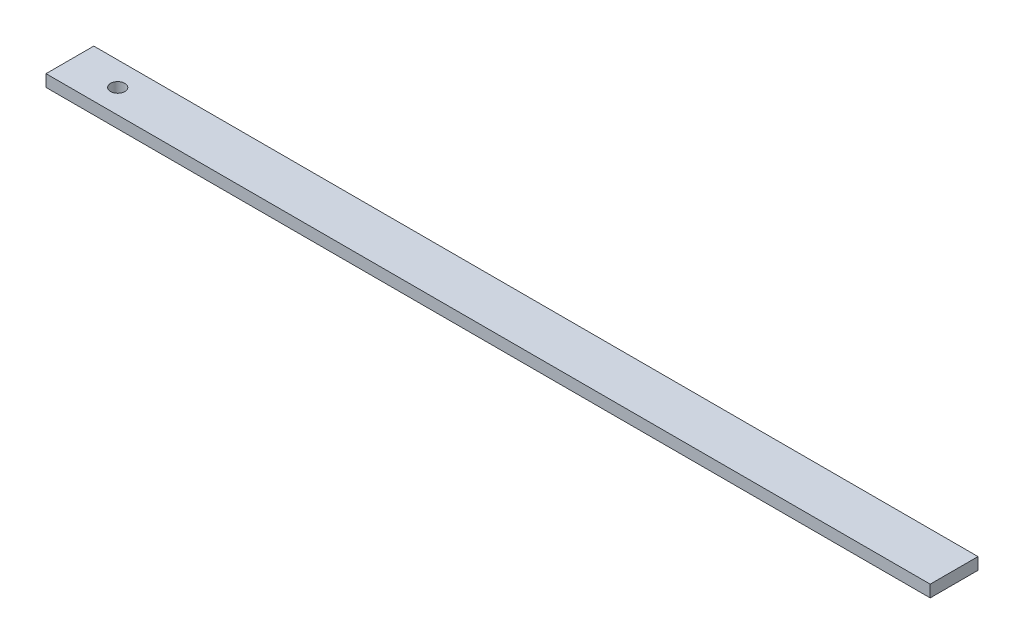
SolidWorks part; units mm, degrees
ref_plane "Front" through (0, 0, 0) normal (0, 0, 1) x (1, 0, 0)
ref_plane "Top" through (0, 0, 0) normal (0, 1, 0) x (1, 0, 0)
ref_plane "Right" through (0, 0, 0) normal (1, 0, 0) x (0, 0, -1)
sketch "Sketch1" plane through (0, 0, 0) normal (1, 0, 0) x (0, 0, -1)
  line L1 (-6.35, 1.5875) -> (6.35, 1.5875)
  line L2 (-6.35, 1.5875) -> (-6.35, -1.5875)
  line L3 (-6.35, -1.5875) -> (6.35, -1.5875)
  line L4 (6.35, 1.5875) -> (6.35, -1.5875)
  line L5 (-6.35, 1.5875) -> (6.35, -1.5875) construction
  line L6 (-6.35, -1.5875) -> (6.35, 1.5875) construction
  point P0 (0, 0)
  dimension "D1" = 12.7
  dimension "D2" = 3.175
extrude "Boss-Extrude1" add sketch "Sketch1" against normal blind 234.95
hole_wizard "#6 Clearance Hole1" positions "Sketch3" profile "Sketch2" hole size "#6" standard "ANSI Inch" end condition through all
sketch "Sketch3" plane through (0, 1.5875, 0) normal (0, 1, 0) x (1, 0, 0)
  line L0 (0, 6.35) -> (0, -6.35) construction
  line L1 (-234.95, -6.35) -> (0, -6.35) construction
  point P0 (-222.25, 0)
  point P3 (0, 0)
  dimension "D1" = 222.25
  dimension "D2" = 6.35
sketch "Sketch2" plane through (-222.25, 1.5875, 0) normal (1, 0, 0) x (0, 0, 1)
  line L0 (0, 0) -> (0, 3.175)
  line L1 (0, 3.175) -> (1.8986, 3.175)
  line L2 (1.8986, 3.175) -> (1.8986, 0)
  line L5 (1.8986, 0) -> (0, 0)
  line L11 (0, -6.35) -> (0, 107.95) construction
  dimension "Thru Hole Dia." = 3.7973
  dimension "Thru Hole Depth" = 3.175
